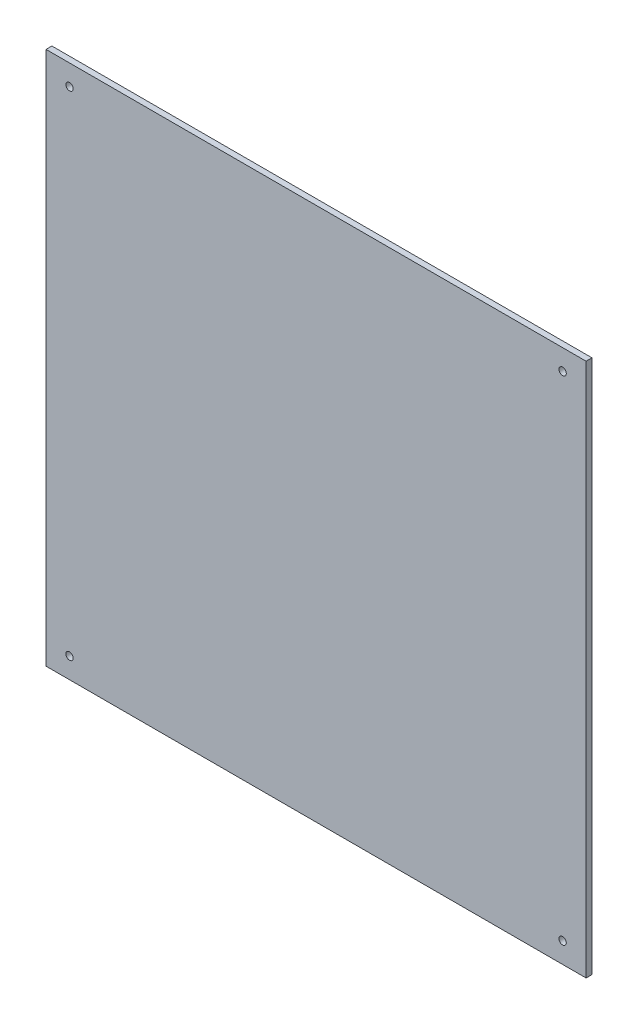
SolidWorks part; units mm, degrees
ref_plane "正面" through (0, 0, 0) normal (0, 0, 1) x (1, 0, 0)
ref_plane "平面" through (0, 0, 0) normal (0, 1, 0) x (1, 0, 0)
ref_plane "右側面" through (0, 0, 0) normal (1, 0, 0) x (0, 0, -1)
sketch "ｽｹｯﾁ1" plane through (0, 0, 0) normal (0, 0, 1) x (1, 0, 0)
  line L1 (0, 0) -> (184, 0)
  line L2 (0, 0) -> (0, 182)
  line L3 (0, 182) -> (184, 182)
  line L4 (184, 0) -> (184, 182)
  dimension "D1" = 182
  dimension "D2" = 184
extrude "ﾎﾞｽ - 押し出し1" add sketch "ｽｹｯﾁ1" along normal blind 2
hole_wizard "M3x0.5 ねじ穴1" positions "ｽｹｯﾁ2" profile "ｽｹｯﾁ3" tap size "M3x0.5" standard "JIS" end condition through all
sketch "ｽｹｯﾁ2" plane through (0, 0, 2) normal (0, 0, 1) x (1, 0, 0)
  line L0 (0, 182) -> (0, 0) construction
  line L2 (0, 0) -> (184, 0) construction
  line L3 (184, 0) -> (184, 182) construction
  line L4 (184, 182) -> (0, 182) construction
  point P0 (8, 175)
  point P2 (8, 7)
  point P4 (176, 7)
  point P6 (176, 175)
  dimension "D1" = 8
  dimension "D2" = 7
  dimension "D3" = 7
  dimension "D4" = 8
  dimension "D5" = 7
  dimension "D6" = 8
  dimension "D7" = 7
  dimension "D8" = 8
  dimension "D9" = 168
  dimension "D10" = 168
sketch "ｽｹｯﾁ3" plane through (8, 175, 2) normal (1, 0, 0) x (0, -1, 0)
  line L0 (0, 0) -> (0, 2)
  line L1 (0, 2) -> (1.25, 2)
  line L2 (1.25, 2) -> (1.25, 0)
  line L5 (1.25, 0) -> (0, 0)
  line L11 (0, -6.35) -> (0, 107.95) construction
  dimension "次ｻｰﾌｪｽまでのねじ下穴ﾄﾞﾘﾙ直径" = 2.5
  dimension "次ｻｰﾌｪｽまでのねじ下穴ﾄﾞﾘﾙの深さ" = 2
cosmetic thread "穴のねじ山1" parameters "D2"=3
cosmetic thread "穴のねじ山2" parameters "D2"=3
cosmetic thread "穴のねじ山3" parameters "D2"=3
cosmetic thread "穴のねじ山4" parameters "D2"=3
ref_plane "平面1" through (92, 0, 0) normal (1, 0, 0) x (0, 0, -1)
ref_plane "平面2" through (0, 91, 0) normal (0, 1, 0) x (1, 0, 0)
